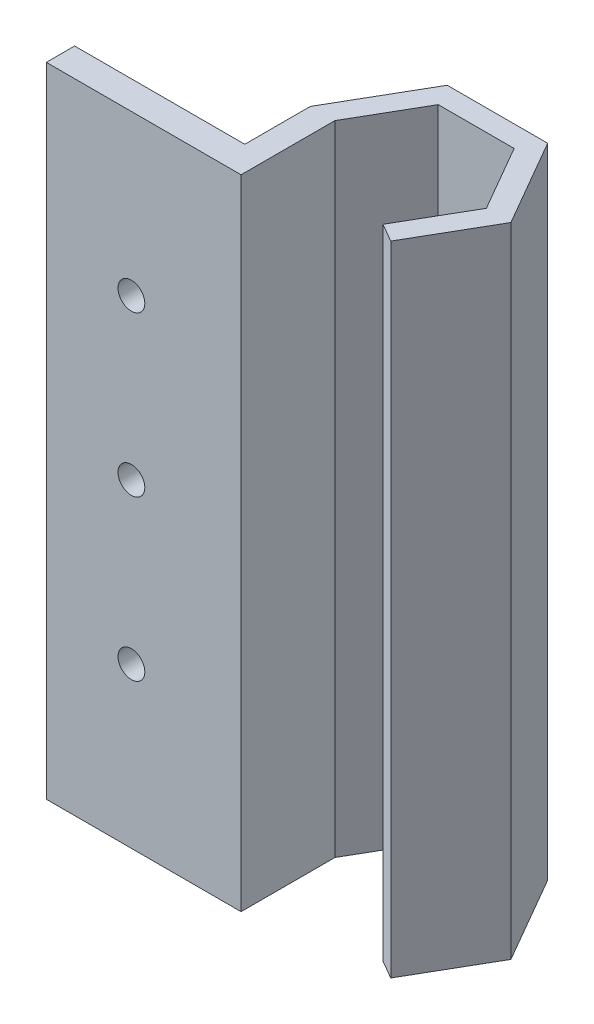
SolidWorks part; units mm, degrees
ref_plane "Front Plane" through (0, 0, 0) normal (0, 0, 1) x (1, 0, 0)
ref_plane "Top Plane" through (0, 0, 0) normal (0, 1, 0) x (1, 0, 0)
ref_plane "Right Plane" through (0, 0, 0) normal (1, 0, 0) x (0, 0, -1)
sketch "Sketch4" plane through (0, 0, 0) normal (0, 1, 0) x (1, 0, 0)
  line L0 (8.9489, -15.4) -> (17.8401, 0)
  line L1 (8.8623, 15.35) -> (-8.8623, 15.35) construction
  line L2 (-8.8623, 15.35) -> (-17.7247, 0) construction
  line L3 (-17.7247, 0) -> (-8.8623, -15.35) construction
  line L4 (-8.8623, -15.35) -> (8.8623, -15.35) construction
  line L5 (8.8623, -15.35) -> (17.7247, 0) construction
  line L6 (17.7247, 0) -> (8.8623, 15.35) construction
  line L7 (17.8401, 0) -> (8.9201, 15.45)
  line L8 (8.9201, 15.45) -> (-8.9201, 15.45)
  line L9 (-8.9201, 15.45) -> (-17.8113, 0.05)
  line L10 (13.2791, -17.9) -> (23.6136, 0)
  line L11 (23.6136, 0) -> (11.8068, 20.45)
  line L12 (11.8068, 20.45) -> (-11.8068, 20.45)
  line L16 (8.9489, -15.4) -> (13.2791, -17.9)
  line L30 (-17.8113, 0.05) -> (-17.8113, -22)
  line L33 (-23.5848, 0.05) -> (-23.5848, -15.35)
  line L35 (-11.8068, 20.45) -> (-23.5848, 0.05)
  line L36 (-11.8068, 20.45) -> (-22.1414, 2.55) construction
  line L39 (-23.5848, -15.35) -> (-63.5848, -15.35)
  line L40 (-63.5848, -22) -> (-63.5848, -15.35)
  line L41 (-63.5848, -22) -> (-17.8113, -22)
  circle A0 centre (0, 0) radius 15.35 construction
  dimension "D2" = 0.1
  dimension "D1" = 30.7
  dimension "D3" = 5.1
  dimension "D4" = 6.65
  dimension "D5" = 22.05
  dimension "D6" = 40
  dimension "D7" = 15.4
  dimension "D8" = 20.4
extrude "Boss-Extrude3" add sketch "Sketch4" against normal blind 150 contours L39 L40 L41 L30 L9 L8 L7 L0 L16 L10 L11 L12 L35 L33
sketch "Sketch5" plane through (0, 0, 15.35) normal (0, 0, -1) x (-1, 0, 0)
  line L0 (43.5848, 0) -> (43.5848, -150) construction
  line L1 (23.5848, 0) -> (63.5848, 0) construction
  line L2 (23.5848, -150) -> (63.5848, -150) construction
  line L3 (63.5848, -75) -> (23.5848, -75) construction
  line L4 (63.5848, -150) -> (63.5848, 0) construction
  line L5 (23.5848, -150) -> (23.5848, 0) construction
  line L6 (23.5848, -75) -> (23.5848, -150) construction
  line L7 (23.5848, -75) -> (23.5848, 0) construction
  line L8 (23.5848, -112.5) -> (63.5848, -112.5) construction
  line L9 (23.5848, -37.5) -> (63.5848, -37.5) construction
  circle A0 centre (43.5848, -37.5) radius 3.15
  circle A1 centre (43.5848, -75) radius 3.15
  circle A2 centre (43.5848, -112.5) radius 3.15
extrude "Cut-Extrude1" cut sketch "Sketch5" against normal blind 10 contours A0 | A1 | A2
